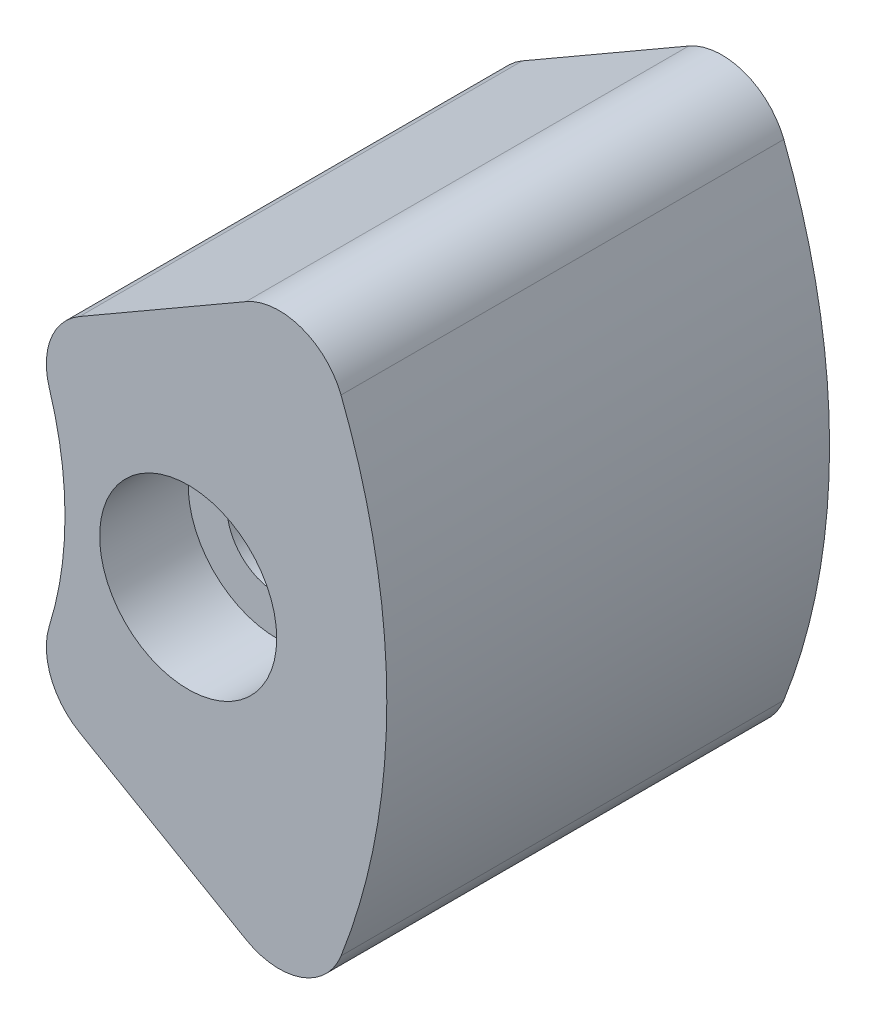
SolidWorks part; units mm, degrees
ref_plane "Plano frontal" through (0, 0, 0) normal (0, 0, 1) x (1, 0, 0)
ref_plane "Plano superior" through (0, 0, 0) normal (0, 1, 0) x (1, 0, 0)
ref_plane "Plano direito" through (0, 0, 0) normal (1, 0, 0) x (0, 0, -1)
sketch "Esboço1" plane through (0, 0, 0) normal (0, 0, 1) x (1, 0, 0)
  line L0 (224.9739, 108.1363) -> (232.4914, 112.4766)
  line L1 (224.9739, 91.8637) -> (232.4914, 87.5234)
  line L3 (216.6756, 95.5) -> (234.4255, 85.2521) construction
  line L4 (234.4255, 114.7479) -> (216.6756, 104.5) construction
  arc A0 (236.7858, 89.0298) -> (236.7858, 110.9702) centre (208.7071, 100) ccw
  arc A1 (223.6099, 95.3545) -> (223.6099, 104.6455) centre (208.7071, 100) ccw
  arc A2 (232.4914, 87.5234) -> (236.7858, 89.0298) centre (233.9914, 90.1215) ccw
  arc A3 (236.7858, 110.9702) -> (232.4914, 112.4766) centre (233.9914, 109.8785) ccw
  arc A4 (223.6099, 95.3545) -> (224.9739, 91.8637) centre (226.4739, 94.4618) ccw
  arc A5 (224.9739, 108.1363) -> (223.6099, 104.6455) centre (226.4739, 105.5382) ccw
  ellipse E0 centre (208.7071, 100) end of major axis (208.7071, 87.5) minor radius 12.4524 construction
  dimension "D3" = 3
  dimension "D1" = 1
  dimension "D2" = 1
extrude "Ressalto-extrusão1" add sketch "Esboço1" along normal up to vertex (20 mm away)
hole_wizard "Rebaixo para SHCS M41" positions "Esboço2" profile "Esboço3" counterbore size "M4" standard "Ansi Metric" end condition through all
sketch "Esboço2" plane through (0, 0, 20) normal (0, 0, 1) x (1, 0, 0)
  point P0 (229.8814, 100)
sketch "Esboço3" plane through (229.8814, 100, 20) normal (1, 0, 0) x (0, -1, 0)
  line L0 (0, 0) -> (0, 20)
  line L1 (0, 20) -> (2.25, 20)
  line L3 (2.25, 20) -> (2.25, 4)
  line L4 (2.25, 4) -> (4, 4)
  line L5 (4, 4) -> (4, 0)
  line L7 (4, 0) -> (0, 0)
  line L11 (0, -6.35) -> (0, 107.95) construction
  dimension "Thru Hole Dia." = 4.5
  dimension "Thru Hole Depth" = 20
  dimension "C'Bore Dia." = 8
  dimension "C'Bore Depth" = 4
